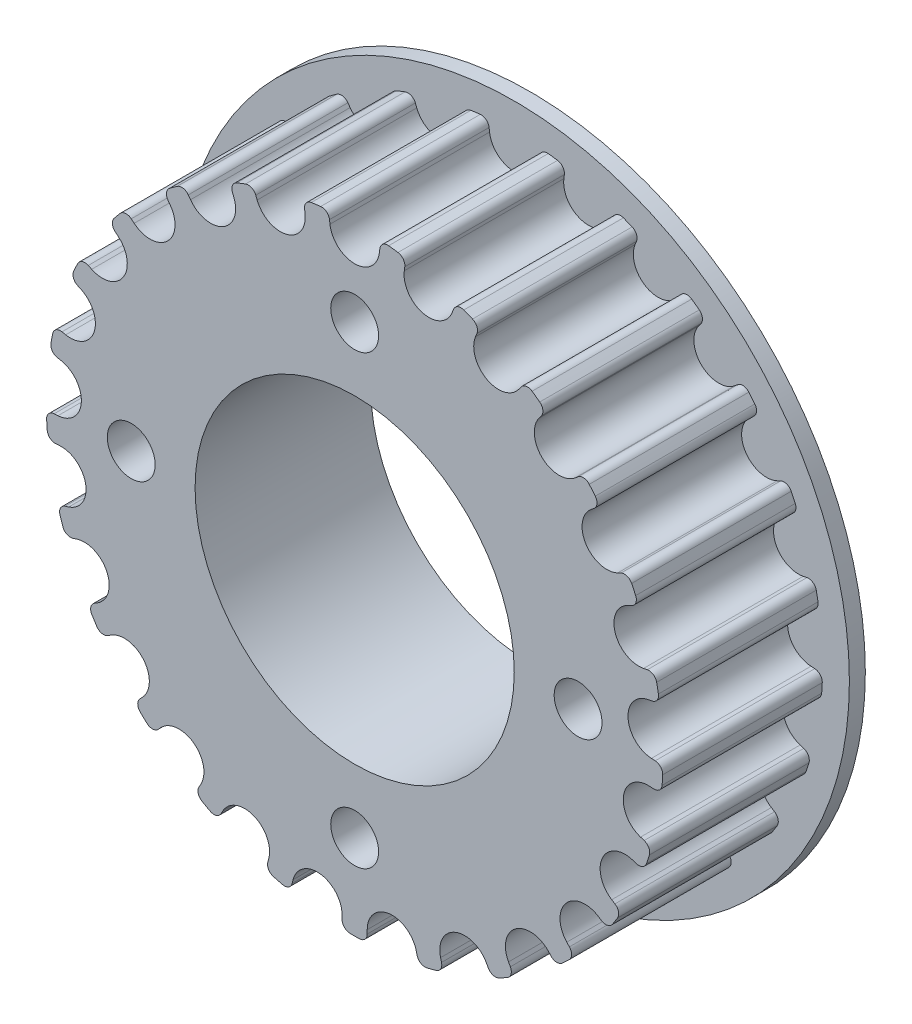
SolidWorks part; units mm, degrees
material "6061 合金"
ref_plane "前视基准面" through (0, 0, 0) normal (0, 0, 1) x (1, 0, 0)
ref_plane "上视基准面" through (0, 0, 0) normal (0, 1, 0) x (1, 0, 0)
ref_plane "右视基准面" through (0, 0, 0) normal (1, 0, 0) x (0, 0, -1)
other "Configuration Table"
sketch "草图1" plane through (0, 0, 0) normal (0, 0, 1) x (1, 0, 0)
  circle A0 centre (0, 0) radius 19.8944
  dimension "P.D" = 39.7887
extrude "凸台-拉伸1" add sketch "草图1" along normal blind 10
sketch "草图2" plane through (0, 0, 10) normal (0, 0, 1) x (1, 0, 0)
  line L0 (0, 19.8944) -> (0, 19.3224) construction
  line L1 (0, 19.3224) -> (0, 0) construction
  line L2 (1.5774, 18.7687) -> (1.5484, 18.5323)
  line L3 (2.4934, 19.7375) -> (2.4217, 19.17)
  line L4 (-2.4934, 19.7375) -> (-2.4217, 19.17)
  line L5 (-1.5774, 18.7687) -> (-1.5484, 18.5323)
  circle A0 centre (0, 0) radius 19.8944 construction
  arc A1 (2.4934, 19.7375) -> (-2.4934, 19.7375) centre (0, 0) ccw
  circle A2 centre (0, 0) radius 19.3224 construction
  arc A3 (-1.5484, 18.5323) -> (1.5484, 18.5323) centre (0, 18.7224) ccw
  arc A4 (2.1288, 19.2047) -> (2.4217, 19.17) centre (0, 0) cw
  arc A5 (1.5774, 18.7687) -> (2.1288, 19.2047) centre (2.0737, 18.7078) cw
  arc A6 (-1.5774, 18.7687) -> (-2.1288, 19.2047) centre (-2.0737, 18.7078) ccw
  arc A7 (-2.1288, 19.2047) -> (-2.4217, 19.17) centre (0, 0) ccw
  point P16 (1.6369, 19.2529)
  point P21 (0, 17.1624)
  dimension "R" = 1.56
  dimension "D3" = 0.5
  dimension "D1" = 7.2
  dimension "D2" = 7
  dimension "H_g" = 2.16
  dimension "delta" = 0.572
extrude "切除-拉伸1" cut sketch "草图2" against normal through all
pattern_circular "阵列(圆周)1" count 25 over 360 about axis through (0, 0, 0) along (0, 0, 1) of "切除-拉伸1"
sketch "草图3" plane through (0, 0, 10) normal (0, 0, 1) x (1, 0, 0)
  circle A0 centre (0, 0) radius 21
  dimension "D1" = 42
extrude "凸台-拉伸3" add sketch "草图3" against normal blind 1 from surface at -10 starting at face at (0, 0, 0)
sketch "草图4" plane through (0, 0, -1) normal (0, 0, -1) x (-1, 0, 0)
  circle A0 centre (0, 0) radius 10
  dimension "D3" = 20
extrude "切除-拉伸3" cut sketch "草图4" against normal through all
sketch "草图5" plane through (0, 0, -1) normal (0, 0, -1) x (-1, 0, 0)
  circle A0 centre (14, 0) radius 1.5
  circle A1 centre (0, -14) radius 1.5
  circle A2 centre (-14, 0) radius 1.5
  circle A3 centre (0, 14) radius 1.5
  point P2 (0, 0)
  point P13 (0, 0)
  dimension "D1" = 3
  dimension "D2" = 14
  dimension "D3" = 4
extrude "切除-拉伸4" cut sketch "草图5" against normal through all
equation "\"P\"= 5'（勿动）"
equation "\"N\"= 25'齿数（5M不小于13）"
equation "\"H\"= 10'齿厚（一般为带宽+2）"
equation "\"R_t\"= 0.5'齿槽圆角（通常无需修改）"
equation "\"P.D@草图1\"= \"P\" * \"N\" / pi'节径"
equation "\"D1@凸台-拉伸1\"=\"H\""
equation "\"D1@草图2\"= 180 / \"N\"'作者：wister"
equation "\"R@草图2\"= 1.56'齿顶圆角"
equation "\"D3@草图2\"=\"R_t\""
equation "\"D1@阵列(圆周)1\"=\"N\""
equation "\"H_g@草图2\"= 2.16'齿槽深"
equation "\"delta@草图2\"= 1.144 / 2'节顶距"
